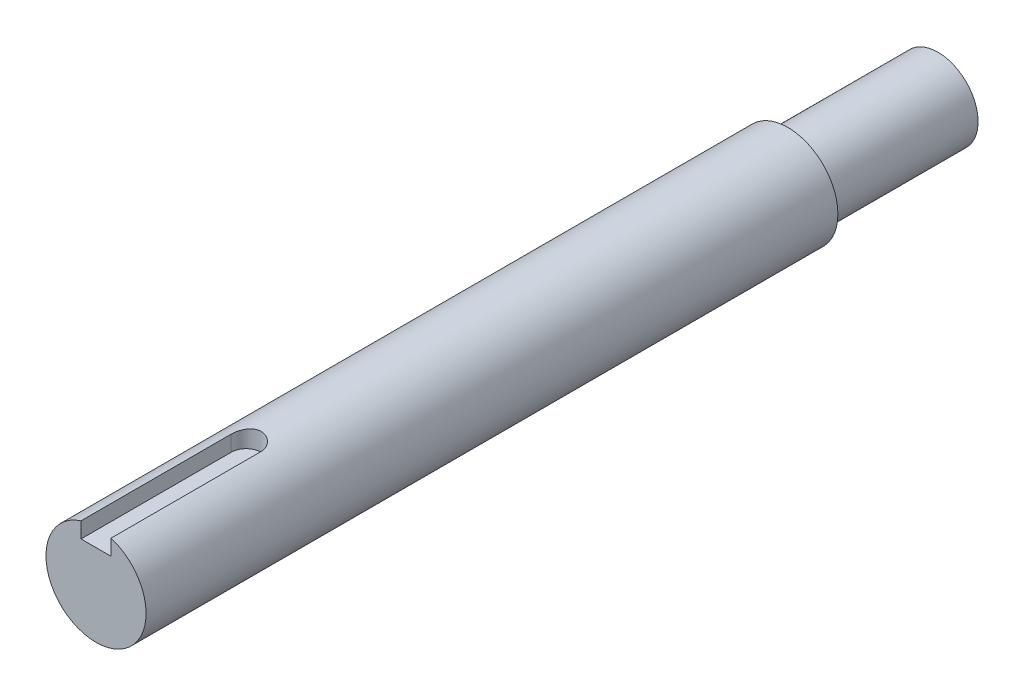
SolidWorks part; units mm, degrees
material "5052-H34"
ref_plane "正面" through (0, 0, 0) normal (0, 0, 1) x (1, 0, 0)
ref_plane "平面" through (0, 0, 0) normal (0, 1, 0) x (1, 0, 0)
ref_plane "右側面" through (0, 0, 0) normal (1, 0, 0) x (0, 0, -1)
sketch "ｽｹｯﾁ1" plane through (0, 0, 0) normal (0, 0, 1) x (1, 0, 0)
  circle A0 centre (0, 0) radius 5
  dimension "D1" = 10
extrude "ﾎﾞｽ - 押し出し1" add sketch "ｽｹｯﾁ1" along normal blind 69.1
sketch "ｽｹｯﾁ3" plane through (0, 0, 0) normal (0, 0, -1) x (-1, 0, 0)
  circle A0 centre (0, 0) radius 4
  dimension "D1" = 8
extrude "ﾎﾞｽ - 押し出し3" add sketch "ｽｹｯﾁ3" along normal blind 15
ref_plane "平面1" through (0, 5, 0) normal (0, 1, 0) x (1, 0, 0)
sketch "ｽｹｯﾁ4" plane through (0, 5, 0) normal (0, 1, 0) x (1, 0, 0)
  line L0 (0, 0) -> (0, -69.1) construction
  line L1 (-5, -69.1) -> (5, -69.1) construction
  line L3 (-1.5, -54.1) -> (1.5, -54.1)
  line L4 (-1.5, -54.1) -> (-1.5, -69.1)
  line L5 (-1.5, -69.1) -> (1.5, -69.1)
  line L6 (1.5, -54.1) -> (1.5, -69.1)
  line L7 (-1.5, -54.1) -> (1.5, -69.1) construction
  line L8 (-1.5, -69.1) -> (1.5, -54.1) construction
  circle A0 centre (0, -54.1) radius 1.5
  point P5 (0, -61.6)
  dimension "D1" = 3
  dimension "D2" = 15
extrude "ｶｯﾄ - 押し出し1" cut sketch "ｽｹｯﾁ4" against normal blind 1.8 contours L3 A0 | L3 A0 | A0 L4 L5 L6
